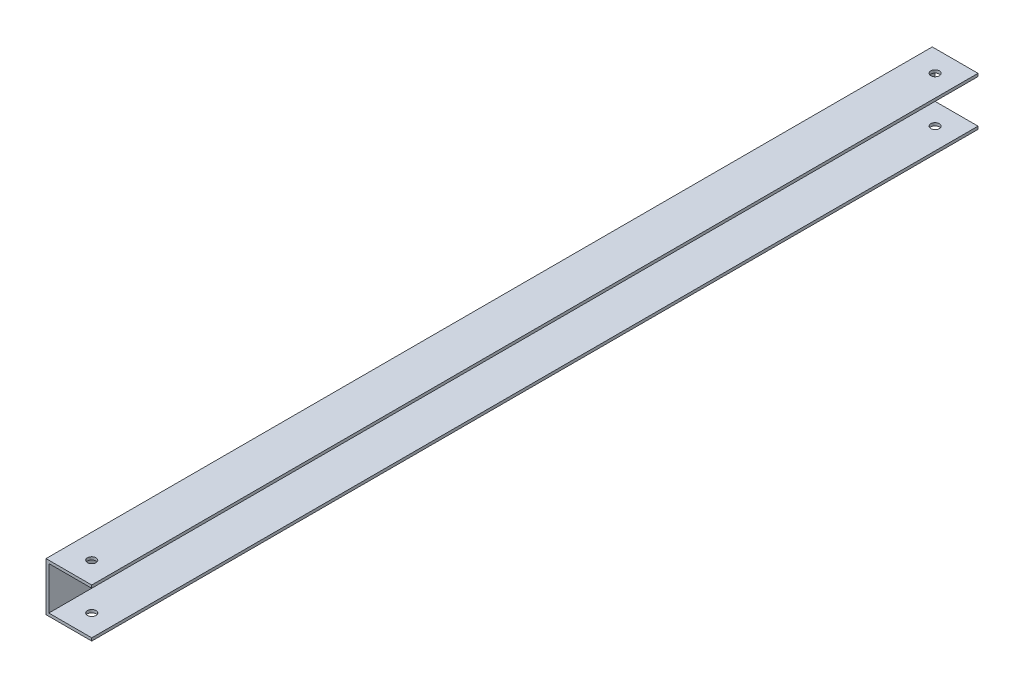
SolidWorks part; units mm, degrees
ref_plane "Front Plane" through (0, 0, 0) normal (0, 0, 1) x (1, 0, 0)
ref_plane "Top Plane" through (0, 0, 0) normal (0, 1, 0) x (1, 0, 0)
ref_plane "Right Plane" through (0, 0, 0) normal (1, 0, 0) x (0, 0, -1)
sketch "Sketch1" plane through (0, 0, 0) normal (0, 0, 1) x (1, 0, 0)
  line L0 (15, 15) -> (15, 17)
  line L1 (-15, -15) -> (15, -15)
  line L2 (-15, -15) -> (-15, 15)
  line L3 (-15, 15) -> (15, 15)
  line L7 (-17, -17) -> (15, -17)
  line L8 (-17, -17) -> (-17, 17)
  line L9 (-17, 17) -> (15, 17)
  line L13 (15, -15) -> (15, -17)
  point P0 (0, 0)
  point P6 (0, 0)
  dimension "D1" = 30
  dimension "D2" = 30
  dimension "D3" = 2
  dimension "D4" = 2
extrude "Boss-Extrude1" add sketch "Sketch1" along normal blind 620
sketch "Sketch2" plane through (0, 17, 0) normal (0, 1, 0) x (1, 0, 0)
  line L0 (15, 0) -> (-17, 0) construction
  line L1 (15, -620) -> (-17, -620) construction
  circle A0 centre (0, -605) radius 3
  circle A1 centre (0, -15) radius 3
  dimension "D1" = 6
  dimension "D2" = 6
  dimension "D3" = 15
  dimension "D4" = 15
extrude "Cut-Extrude1" cut sketch "Sketch2" against normal through all
